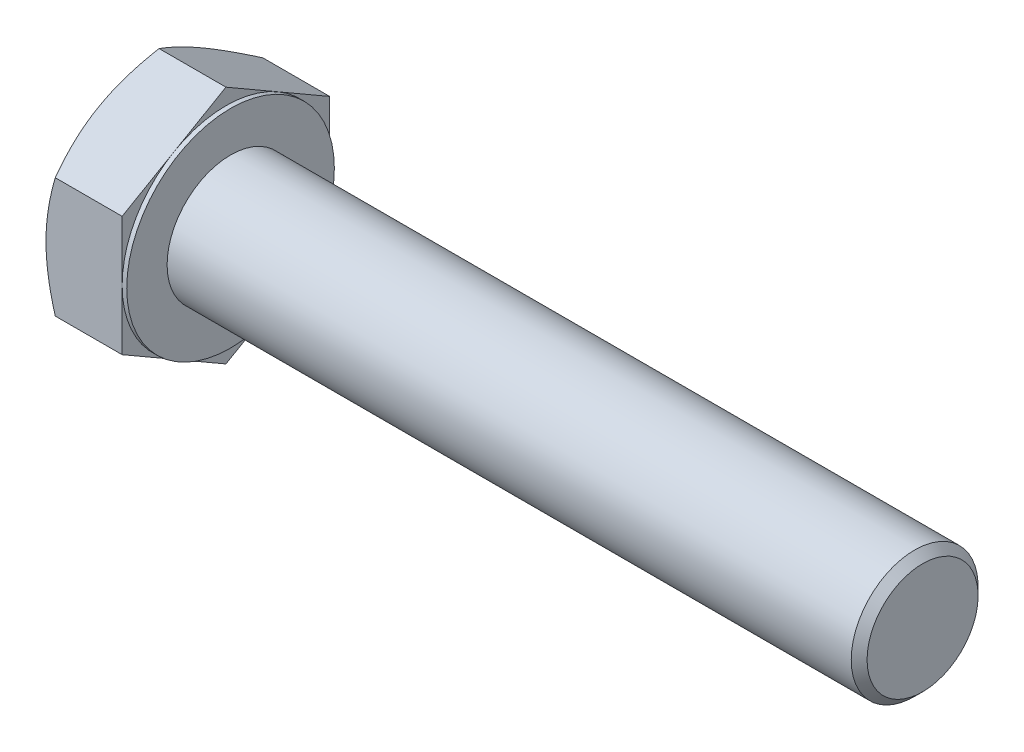
SolidWorks part; units mm, degrees
ref_plane "Plane1" through (0, 0, 0) normal (0, 0, 1) x (1, 0, 0)
ref_plane "Plane2" through (0, 0, 0) normal (0, 1, 0) x (1, 0, 0)
ref_plane "Plane3" through (0, 0, 0) normal (1, 0, 0) x (0, 0, -1)
sketch "Sketch1" plane through (0, 0, 0) normal (1, 0, 0) x (0, 0, -1)
  line L0 (18, 10.3923) -> (18, -10.3923)
  line L1 (-18, 10.3923) -> (-18, -10.3923)
  line L2 (18, -10.3923) -> (0, -20.7846)
  line L3 (0, -20.7846) -> (-18, -10.3923)
  line L4 (18, 10.3923) -> (0, 20.7846)
  line L5 (0, 20.7846) -> (-18, 10.3923)
  dimension "Width_flats" = 36
  dimension "D2" = 120
  dimension "D3" = 18
  dimension "D4" = 18
  dimension "D5" = 18
extrude "BaseHead" add sketch "Sketch1" along normal blind 14
sketch "BodySke" plane through (0, 0, 0) normal (0, 0, 1) x (1, 0, 0)
  line L0 (0, 10.3923) -> (0, -10.3923) construction
  line L1 (0, 0) -> (134, 0)
  line L2 (0, 0) -> (0, 11)
  line L3 (0, 11) -> (132.626, 11)
  line L4 (134, 0) -> (134, 9.626)
  line L5 (14, 20.7846) -> (14, 10.3923) construction
  line L6 (134, 9.626) -> (132.626, 11)
  line L7 (0, 0) -> (96.52, 0) construction
  line L8 (134, -9.626) -> (132.626, -11) construction
  line L9 (0, -11) -> (132.626, -11) construction
  line L10 (16.5, 15.24) -> (16.5, -1.27) construction
  line L11 (89, 15.24) -> (89, -1.27) construction
  line L12 (14, 10.3923) -> (14, -10.3923) construction
  dimension "Length" = 120
  dimension "Body_ch_ang" = 45
  dimension "Diameter" = 22
  dimension "Minor_dia" = 19.252
  dimension "Advance" = 2.5
  dimension "Thread_nom" = 45
revolve "BaseBody" add sketch "BodySke"
cosmetic thread "ThreadCosmetic" [suppressed]
fillet "HeadFillet" [suppressed] radius 0.8
sketch "Sketch3" plane through (0, 0, 0) normal (0, 0, 1) x (1, 0, 0)
  line L0 (0, 18) -> (4.4944, 25.7846)
  line L1 (0, 20.7846) -> (0, 10.3923) construction
  line L2 (4.4944, 25.7846) -> (4.4944, 30.7846)
  line L3 (4.4944, 30.7846) -> (-10, 30.7846)
  line L4 (-10, 30.7846) -> (-10, 18)
  line L5 (-10, 18) -> (0, 18)
  line L6 (0, 0) -> (99.06, 0) construction
  line L7 (14, 20.7846) -> (0, 20.7846) construction
  dimension "D1" = 18
  dimension "D2" = 5
  dimension "D3" = 10
  dimension "D4" = 5
  dimension "Head_ch_ang" = 30
revolve "HeadChamfer" cut sketch "Sketch3" angle 360 about L6
sketch "Sketch5" plane through (0, 0, 0) normal (0, 0, 1) x (1, 0, 0)
  line L0 (14, 18) -> (9.5056, 25.7846)
  line L1 (14, 20.7846) -> (14, 10.3923) construction
  line L2 (9.5056, 25.7846) -> (9.5056, 30.7846)
  line L3 (9.5056, 30.7846) -> (19.5056, 30.7846)
  line L4 (19.5056, 30.7846) -> (19.5056, 18)
  line L5 (19.5056, 18) -> (14, 18)
  line L7 (14, 20.7846) -> (1.6077, 20.7846) construction
  line L8 (0, 0) -> (99.06, 0) construction
  line L9 (0, 0) -> (99.06, 0) construction
  dimension "D1" = 18
  dimension "D2" = 5
  dimension "D3" = 10
  dimension "Head_ch_ang" = 30
  dimension "D4" = 5
revolve "UnderHeadChamfer" [suppressed] cut sketch "Sketch5" angle 360 about L8
sketch "Sketch4" plane through (0, 0, 0) normal (0, 0, 1) x (1, 0, 0)
  line L1 (14, 20.7846) -> (14, 10.3923) construction
  line L2 (14, 18) -> (13.2, 18)
  line L3 (14, 18) -> (14, 30.7846)
  line L4 (14, 30.7846) -> (13.2, 30.7846)
  line L5 (0, 0) -> (95.25, 0) construction
  line L6 (0, 0) -> (96.52, 0) construction
  line L7 (13.2, 18) -> (13.2, 30.7846)
  line L8 (14, 20.7846) -> (1.6077, 20.7846) construction
  dimension "D1" = 36
  dimension "D2" = 10
  dimension "Bearing_ht" = 0.8
revolve "BearingFace" cut sketch "Sketch4" angle 360 about L5
sketch "ThdSchSke" plane through (0, 0, 0) normal (0, 0, 1) x (1, 0, 0)
  line L0 (89, -9.626) -> (88.0379, -11)
  line L1 (89, -9.626) -> (89.9621, -11)
  line L2 (89.9621, -11) -> (89.9621, -13.75)
  line L3 (-3.175, 0) -> (5.1513, 0) construction
  line L5 (89.9621, -13.75) -> (88.0379, -13.75)
  line L6 (88.0379, -13.75) -> (88.0379, -11)
  dimension "Thread_minor" = 19.252
  dimension "Diameter" = 22
  dimension "Start" = 89
  dimension "SideAngle" = 55
  dimension "VeeAngle" = 70
  dimension "Overcut" = 27.5
revolve "ThreadSchematic" [suppressed] cut sketch "ThdSchSke" angle 360 about L3
pattern_linear "ThdSchPat" [suppressed]
equation "\"D3@Sketch1\" = \"Width_flats@Sketch1\" / 2"
equation "\"D4@Sketch1\" = \"D3@Sketch1\""
equation "\"D5@Sketch1\" = \"D4@Sketch1\""
equation "\"Thread_minor@ThreadCosmetic\" = \"Minor_dia@BodySke\""
equation "\"D1@Sketch3\" = \"Width_flats@Sketch1\" / 2"
equation "\"D1@Sketch5\" = \"Width_flats@Sketch1\" / 2"
equation "\"Head_ch_ang@Sketch5\" = \"Head_ch_ang@Sketch3\""
equation "\"D1@Sketch4\" = \"Width_flats@Sketch1\""
equation "\"Thread_length@ThreadCosmetic\" = ((sgn( (\"Length@BodySke\" - \"Advance@BodySke\" ) - \"Thread_nom@BodySke\" )-1)*( (\"Length@BodySke\" - \"Advance@BodySke\" ) - \"Thread_nom@BodySke\" ))/-2+ \"Thread_nom@BodySke\""
equation "\"Thread_minor@ThdSchSke\" = \"Minor_dia@BodySke\""
equation "\"Diameter@ThdSchSke\" = \"Diameter@BodySke\""
equation "\"Overcut@ThdSchSke\" = \"Diameter@BodySke\" * 1.25"
equation "\"Start@ThdSchSke\" = \"Head_ht@BaseHead\" + \"Length@BodySke\" - \"Thread_length@ThreadCosmetic\"  '---Non-countersunk---"
equation "\"Num_threads@ThdSchPat\" = int( \"Thread_length@ThreadCosmetic\" / \"Advance@BodySke\" + 0.999 )  + 1"
equation "\"Advance@ThdSchPat\" = \"Thread_length@ThreadCosmetic\" /  (\"Num_threads@ThdSchPat\" - 1) 'relax it"
equation "\"Num_threads@ThdSchPat\" = \"Num_threads@ThdSchPat\" - sgn( \"Num_threads@ThdSchPat\" - 1) '---chamfered tips only---"
